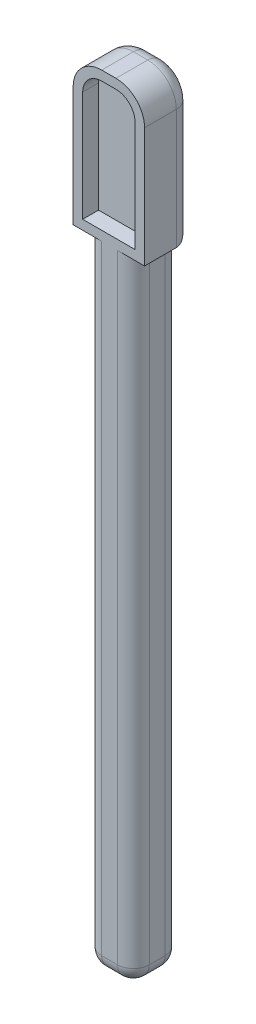
SolidWorks part; units mm, degrees
ref_plane "前视基准面" through (0, 0, 0) normal (0, 0, 1) x (1, 0, 0)
ref_plane "上视基准面" through (0, 0, 0) normal (0, 1, 0) x (1, 0, 0)
ref_plane "右视基准面" through (0, 0, 0) normal (1, 0, 0) x (0, 0, -1)
sketch "草图1" plane through (0, 0, 0) normal (0, 0, 1) x (1, 0, 0)
  line L0 (3, 40) -> (3.7031, 40)
  line L1 (0, 0) -> (3, 0)
  line L2 (0, 0) -> (0, 40)
  line L4 (3, 0) -> (3, 40)
  line L5 (-0.7969, 40) -> (0, 40)
  line L6 (-0.7969, 40) -> (-0.7969, 47.5462)
  line L7 (1.0031, 49.3462) -> (1.9031, 49.3462)
  line L8 (3.7031, 40) -> (3.7031, 47.5462)
  arc A0 (1.9031, 49.3462) -> (3.7031, 47.5462) centre (1.9031, 47.5462) cw
  arc A1 (1.0031, 49.3462) -> (-0.7969, 47.5462) centre (1.0031, 47.5462) ccw
  point P11 (3.7031, 49.3462)
  point P14 (-0.7969, 49.3462)
  dimension "D4" = 1.8
  dimension "D1" = 3
  dimension "D2" = 40
  dimension "D3" = 4.5
extrude "凸台-拉伸1" add sketch "草图1" along normal blind 3
sketch "草图2" plane through (0, 0, 3) normal (0, 0, 1) x (1, 0, 0)
  line L0 (-0.7969, 47.5462) -> (-0.7969, 40) construction
  line L1 (3.7031, 40) -> (3.7031, 47.5462) construction
  line L2 (1.9031, 49.3462) -> (1.0031, 49.3462) construction
  line L3 (3.7031, 40) -> (3.7031, 47.5462) construction
  line L4 (-0.7969, 47.5462) -> (-0.7969, 40) construction
  line L5 (1.9031, 49.3462) -> (1.0031, 49.3462) construction
  line L6 (-0.7969, 40) -> (3.7031, 40) construction
  line L7 (3.1031, 40.6) -> (3.1031, 47.5462)
  line L8 (1.9031, 48.7462) -> (1.0031, 48.7462)
  line L9 (-0.1969, 47.5462) -> (-0.1969, 40.6)
  line L10 (-0.1969, 40.6) -> (3.1031, 40.6)
  arc A0 (1.0031, 49.3462) -> (-0.7969, 47.5462) centre (1.0031, 47.5462) ccw construction
  arc A1 (3.7031, 47.5462) -> (1.9031, 49.3462) centre (1.9031, 47.5462) ccw construction
  arc A2 (3.7031, 47.5462) -> (1.9031, 49.3462) centre (1.9031, 47.5462) ccw construction
  arc A3 (1.0031, 49.3462) -> (-0.7969, 47.5462) centre (1.0031, 47.5462) ccw construction
  arc A4 (3.1031, 47.5462) -> (1.9031, 48.7462) centre (1.9031, 47.5462) ccw
  arc A5 (1.0031, 48.7462) -> (-0.1969, 47.5462) centre (1.0031, 47.5462) ccw
  dimension "D1" = 0.6
extrude "切除-拉伸1" cut sketch "草图2" against normal blind 1
fillet "圆角3" radius 1 15 edges at (1.5, 0, 0) (3.3515, 40, 0) (-0.3985, 40, 0) (0, 20, 0) (-0.7969, 43.7731, 0) (1.4531, 49.3462, 0) (-0.2697, 48.8189, 0) (3.1759, 48.8189, 0) (3.7031, 43.7731, 0) (3, 20, 0) (3, 0, 1.5) (0, 0, 1.5) (1.5, 0, 3) (0, 20, 3) (3, 20, 3)
